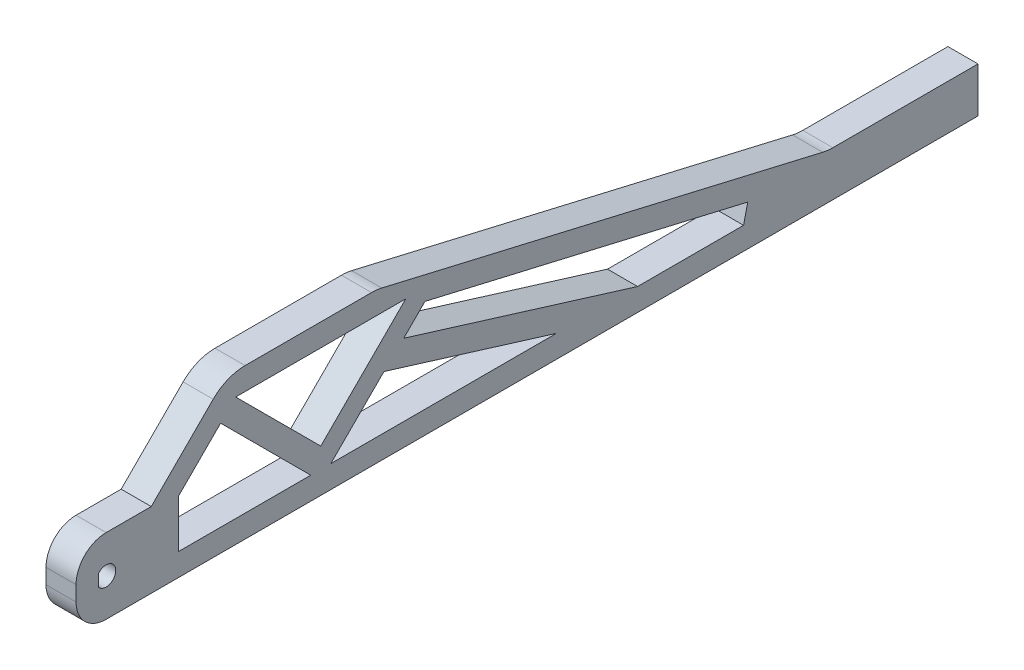
SolidWorks part; units mm, degrees
ref_plane "Front Plane" through (0, 0, 0) normal (0, 0, 1) x (1, 0, 0)
ref_plane "Top Plane" through (0, 0, 0) normal (0, 1, 0) x (1, 0, 0)
ref_plane "Right Plane" through (0, 0, 0) normal (1, 0, 0) x (0, 0, -1)
ref_plane "Plane1" through (0, 0, 0) normal (1, 0, 0) x (0, 0, -1)
sketch "Sketch1" plane through (0, 0, 0) normal (1, 0, 0) x (0, 0, -1)
  line L0 (0, 0) -> (300, 0)
  line L1 (300, 0) -> (300, 15)
  line L2 (300, 15) -> (250, 15)
  line L3 (250, 15) -> (100, 50)
  line L7 (25, 25) -> (50, 50)
  line L8 (50, 50) -> (100, 50)
  line L9 (0, 0) -> (0, 25)
  line L10 (0, 25) -> (25, 25)
  dimension "D1" = 300
  dimension "D2" = 15
  dimension "D3" = 25
  dimension "D4" = 50
  dimension "D5" = 150
  dimension "D6" = 25
  dimension "D7" = 25
  dimension "D8" = 25
extrude "Boss-Extrude1" add sketch "Sketch1" against normal blind 10
sketch "Sketch2" plane through (0, 0, 0) normal (1, 0, 0) x (0, 0, -1)
  line L0 (53.1066, 42.5) -> (109.6751, 42.5)
  line L1 (109.6751, 42.5) -> (81.3909, 14.2157)
  line L2 (81.3909, 14.2157) -> (53.1066, 42.5)
  line L3 (34.1066, 23.5) -> (34.1066, 7.5)
  line L4 (34.1066, 7.5) -> (78.0519, 7.5)
  line L6 (78.0519, 7.5) -> (48.0792, 37.4726)
  line L7 (48.0792, 37.4726) -> (34.1066, 23.5)
  line L8 (102.4076, 25.1777) -> (84.7299, 7.5)
  line L9 (84.7299, 7.5) -> (159.7443, 7.5)
  line L10 (159.7443, 7.5) -> (102.4076, 25.1777)
  line L11 (116.0525, 38.553) -> (223.4223, 13.5)
  line L12 (223.4223, 13.5) -> (222.0223, 7.5)
  line L13 (222.0223, 7.5) -> (186.7656, 7.5)
  line L15 (186.7656, 7.5) -> (108.9814, 31.4819)
  line L17 (250, 15) -> (100, 50) construction
  line L18 (0, 0) -> (300, 0) construction
  line L19 (108.9814, 31.4819) -> (116.0525, 38.553)
  line L20 (7.46, 14.4464) -> (7.46, 10.5536)
  line L21 (50, 50) -> (25, 25) construction
  line L22 (100, 50) -> (50, 50) construction
  line L23 (13.2, 17.0521) -> (13.2, 7.8168) construction
  line L24 (0, 0) -> (300, 0) construction
  line L25 (50, 50) -> (25, 25) construction
  line L26 (0, 25) -> (0, 0) construction
  line L27 (25, 25) -> (0, 25) construction
  arc A0 (7.46, 10.5536) -> (7.46, 14.4464) centre (10, 12.5) ccw
  point P34 (78.0519, 7.5)
  point P35 (48.6708, 38.0642)
  point P36 (156.5271, 20.3879)
  point P37 (159.0076, 16.814)
  point P38 (177.2285, 7.5)
  dimension "D12" = 6.4
  dimension "D1" = 7.5
  dimension "D2" = 7.5
  dimension "D3" = 7.5
  dimension "D4" = 7.5
  dimension "D5" = 60
  dimension "D6" = 25
  dimension "D7" = 7.5
  dimension "D8" = 7.5
  dimension "D9" = 7.5
  dimension "D10" = 16
  dimension "D11" = 7.5
  dimension "D13" = 45
  dimension "D14" = 45
  dimension "D15" = 7.5
  dimension "D16" = 7.5
  dimension "D17" = 7.5
  dimension "D18" = 7.5
  dimension "D19" = 10
  dimension "D22" = 40
  dimension "D23" = 6
  dimension "D24" = 5.74
  dimension "D25" = 10
  dimension "D26" = 12.5
extrude "Cut-Extrude2" cut sketch "Sketch2" against normal through all
fillet "Fillet1" radius 10 2 edges at (-5, 0, 0) (-5, 25, 0)
fillet "Fillet2" radius 15 3 edges at (-5, 15, -250) (-5, 50, -100) (-5, 50, -50)
